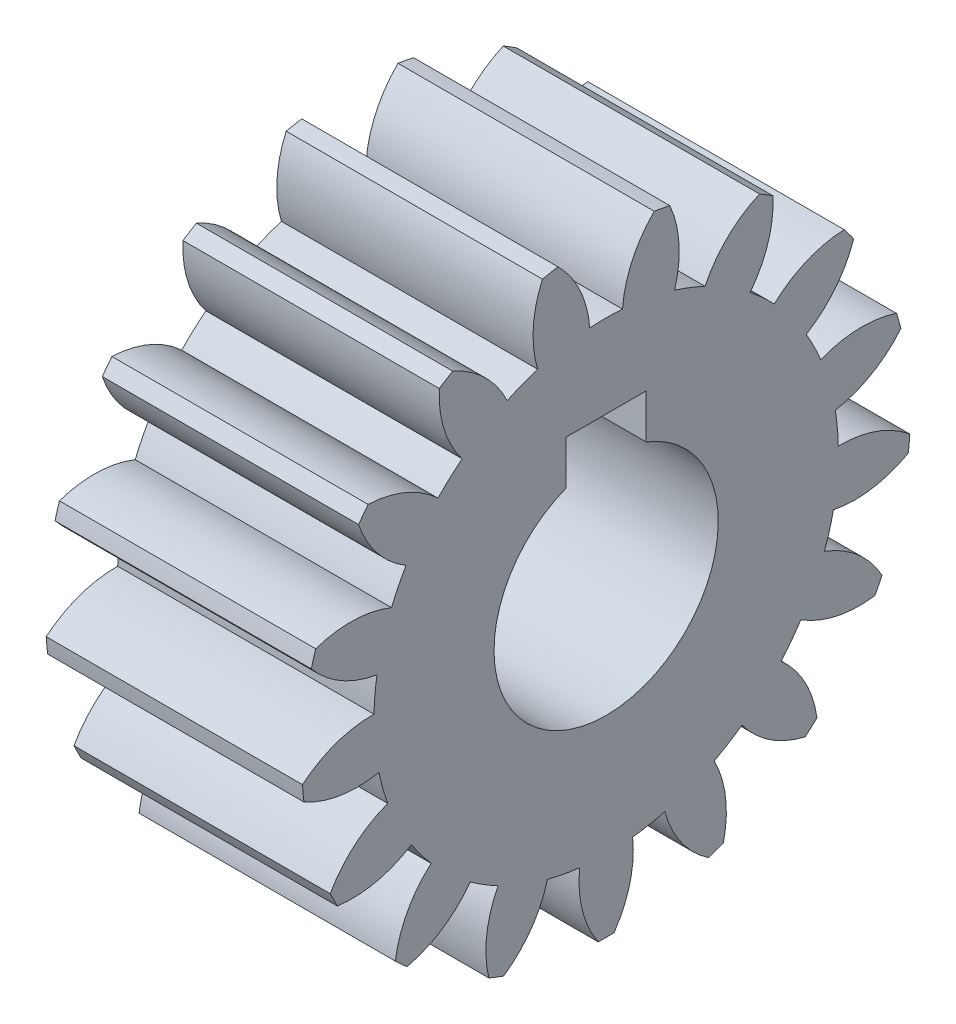
SolidWorks part; units mm, degrees
ref_plane "Plane1" through (0, 0, 0) normal (0, 0, 1) x (1, 0, 0)
ref_plane "Plane2" through (0, 0, 0) normal (0, 1, 0) x (1, 0, 0)
ref_plane "Plane3" through (0, 0, 0) normal (1, 0, 0) x (0, 0, -1)
sketch "HoldingSke" plane through (0, 0, 0) normal (0, 1, 0) x (1, 0, 0)
  line L0 (0, 0) -> (0.4782, -0.1462)
  line L1 (-15, 0) -> (100, 0) construction
  line L2 (0, 0) -> (-2.1039, 2.3779)
  line L3 (0, 0) -> (-11.863, 4.5341)
  line L4 (0, 0) -> (8.2586, 2.5249)
  line L5 (0, 0) -> (-46.8476, -17.4728)
  line L6 (0, 0) -> (-13.2634, -8.9489)
  line L7 (-2.1039, 2.3779) -> (8.6586, 51.2059)
  line L8 (-76.2, 54.61) -> (-73.9, 54.61)
  line L9 (-71.009, 38.7566) -> (-53.1078, 45.2721)
  line L10 (-76.2, 71.12) -> (104.1128, 71.12)
  line L11 (0, 0) -> (-16, 0)
  line L12 (-76.2, 101.6) -> (-76.133, 101.6)
  line L13 (24.9733, 27.94) -> (52.9518, 28.4284)
  line L14 (24.9733, 27.94) -> (24.9743, 27.94)
  line L15 (24.9733, 27.94) -> (100.4006, 29.5858)
  line L16 (-63.627, -2) -> (-12.827, -2)
  circle A0 centre (0, 0) radius 7
  circle A1 centre (0, 0) radius 14.499
  circle A2 centre (0, 0) radius 37.5
  circle A3 centre (0, 0) radius 7
  dimension "MHD" = 28.998
  dimension "Hub_dia" = 75
  dimension "Bore" = 14
  dimension "MBD" = 14
  dimension "Num_teeth" = 17
  dimension "Pitch" = 0.5
  dimension "Overall_len" = 50
  dimension "Show_teeth" = 17
  dimension "Thickness" = 16
  dimension "OAL" = 50.0001
  dimension "T_dim" = 2.3
  dimension "Ap" = 20
  dimension "H" = 19.05
  dimension "Pitch_radius" = 180.3128
  dimension "Width" = 16
  dimension "Backlash" = 0.067
  dimension "Addendum_fac" = 1
  dimension "Dedendum_fac" = 1.25
  dimension "Clearance_fac" = 0.25
  dimension "Dedendum_add" = 0.001
  dimension "Module" = 2
sketch "BasProSke" plane through (0, 0, 0) normal (0, 1, 0) x (1, 0, 0)
  line L0 (-10, 0) -> (60, 0) construction
  line L1 (0, 0) -> (0, 19)
  line L2 (0, 0) -> (16, 0)
  line L3 (16, 0) -> (16, 19)
  line L4 (16, 19) -> (0, 19)
  dimension "Thickness" = 16
  dimension "Diameter" = 38
revolve "Base-Revolve" add sketch "BasProSke" angle 360 about L0
sketch "TooCutSke" plane through (0, 0, 0) normal (1, 0, 0) x (0, 0, -1)
  line L1 (0, 0) -> (0, 107) construction
  line L2 (0, 0) -> (-1.6857, 16.9162) construction
  line L3 (0, 0) -> (-6.2247, 33.2991) construction
  line L4 (-1.6857, 16.9162) -> (-3.1123, 16.6495) construction
  arc A0 (1.0204, 14.4631) -> (-1.0204, 14.4631) centre (0, 0) ccw
  arc A1 (3.0261, 18.7832) -> (-3.0261, 18.7832) centre (0, 0) ccw
  circle A2 centre (0, 0) radius 17 construction
  circle A3 centre (0, 0) radius 15.9748 construction
  arc A4 (-1.0204, 14.4631) -> (-3.0261, 18.7832) centre (-7.8003, 13.9409) ccw
  arc A5 (3.0261, 18.7832) -> (1.0204, 14.4631) centre (7.8003, 13.9409) ccw
  dimension "Root_dia" = 28.998
  dimension "Overcut_dia" = 38.0508
  dimension "Pitch_dia" = 34
  dimension "Base_dia" = 31.9495
  dimension "Flank_rad" = 6.8
  dimension "Half_ang" = 10.588
  dimension "Half_CT" = 1.4513
extrude "ToothCut" cut sketch "TooCutSke" along normal through all
fillet "Breaks" [suppressed] radius 0.04
fillet "RootFillets" [suppressed] radius 0.501
pattern_circular "TeethCuts" count 17 every 21.176 about axis through (-10, 0, 0) along (1, 0, 0) of "ToothCut", "RootFillets", "Breaks"
sketch "HubNeaOneSke" plane through (0, 0, 0) normal (-1, 0, 0) x (0, 0, 1)
  circle A0 centre (0, 0) radius 14.499
  dimension "Diameter" = 28.998
extrude "HubNearOne" [suppressed] add sketch "HubNeaOneSke" along normal blind 34.0001
sketch "HubNeaBotSke" plane through (0, 0, 0) normal (-1, 0, 0) x (0, 0, 1)
  circle A0 centre (0, 0) radius 14.499
  dimension "Diameter" = 28.998
extrude "HubNearBoth" [suppressed] add sketch "HubNeaBotSke" along normal blind 17
ref_plane "FarPln" through (16, 0, 0) normal (1, 0, 0) x (0, 0, -1)
sketch "HubFarSke" plane through (16, 0, 0) normal (1, 0, 0) x (0, 0, -1)
  circle A0 centre (0, 0) radius 14.499
  dimension "Diameter" = 28.998
extrude "HubFar" [suppressed] add sketch "HubFarSke" along normal blind 17
sketch "BorSke" plane through (0, 0, 0) normal (1, 0, 0) x (0, 0, -1)
  circle A0 centre (0, 0) radius 7
  dimension "Diameter" = 14
extrude "Bore" cut sketch "BorSke" along normal mid plane 100.0001
sketch "KeySke" plane through (0, 0, 0) normal (1, 0, 0) x (0, 0, -1)
  line L0 (-2.5, 0) -> (-2.5, 9.3)
  line L1 (-2.5, 9.3) -> (2.5, 9.3)
  line L2 (2.5, 9.3) -> (2.5, 0)
  line L3 (0, 0) -> (0, 34) construction
  line L4 (-2.5, 0) -> (2.5, 0)
  dimension "Offset" = 9.3
  dimension "Width" = 5
extrude "Keyway" cut sketch "KeySke" along normal mid plane 100.0001
pattern_circular "Keyway2" [suppressed] count 2 every 90 about axis through (-10, 0, 0) along (1, 0, 0)
equation "' \"Module@HoldingSke\" = 6.35"
equation "' \"Num_teeth@HoldingSke\" = 12"
equation "' \"Ap@HoldingSke\" =  20"
equation "' \"Ap@HoldingSke\" = 20"
equation "' \"Width@HoldingSke\" = 0.5 * 25.4"
equation "' \"Hub_dia@HoldingSke\"= 1 * 25.4"
equation "' \"Hub_dia@HoldingSke\" = 1 * 25.4"
equation "' \"Overall_len@HoldingSke\" = 1.0 * 25.4"
equation "' \"Bore@HoldingSke\" = 0.75 * 25.4"
equation "' \"T_dim@HoldingSke\" = 0.1 * 25.4"
equation "' \"Width@KeySke\" = 0.25 * 25.4"
equation "' \"Show_teeth@HoldingSke\" = 13"
equation "' \"Backlash@HoldingSke\" = 0.009 * 25.4"
equation "' \"Addendum_fac@HoldingSke\" = 1.0"
equation "' \"Dedendum_fac@HoldingSke\" = 1.25"
equation "' \"Dedendum_add@HoldingSke\" = 0.00005 * 25.4"
equation "' \"Clearance_fac@HoldingSke\" = 0.25"
equation "\"Pitch@HoldingSke\" = 1 / \"Module@HoldingSke\""
equation "\"Overcut_dia@TooCutSke\" = (\"Num_teeth@HoldingSke\" + 2 * \"Addendum_fac@HoldingSke\") / \"Pitch@HoldingSke\" + 0.002 * 25.4"
equation "\"Pitch_dia@TooCutSke\" = \"Num_teeth@HoldingSke\" / \"Pitch@HoldingSke\""
equation "\"Base_dia@TooCutSke\" = \"Num_teeth@HoldingSke\" / \"Pitch@HoldingSke\" * cos((\"Ap@HoldingSke\"  * 3.14159265 / 180))"
equation "\"Root_dia@TooCutSke\" = (\"Num_teeth@HoldingSke\" + 2) / \"Pitch@HoldingSke\" - 2 * (\"Addendum_fac@HoldingSke\" + \"Dedendum_fac@HoldingSke\") / \"Pitch@HoldingSke\" - \"Dedendum_add@HoldingSke\" * 2"
equation "\"Half_ang@TooCutSke\" = 180 / \"Num_teeth@HoldingSke\""
equation "\"Half_CT@TooCutSke\" = \"Num_teeth@HoldingSke\" / \"Pitch@HoldingSke\" * sin((3.14159265 / 2 / \"Num_teeth@HoldingSke\")) / 2 - 7 * \"Backlash@HoldingSke\" / 4"
equation "\"Flank_rad@TooCutSke\" = \"Num_teeth@HoldingSke\" / \"Pitch@HoldingSke\" / 5"
equation "\"Radius@RootFillets\" = \"Clearance_fac@HoldingSke\" / \"Pitch@HoldingSke\" + \"Dedendum_add@HoldingSke\""
equation "\"Break_rad@Breaks\" = 0.02 / \"Pitch@HoldingSke\""
equation "\"Thickness@HoldingSke\" = \"Width@HoldingSke\""
equation "\"OAL@HoldingSke\" = \"Thickness@HoldingSke\""
equation "\"MHD@HoldingSke\" = (\"Num_teeth@HoldingSke\" + 2) / \"Pitch@HoldingSke\" - 2 * (\"Addendum_fac@HoldingSke\" + \"Dedendum_fac@HoldingSke\")  / \"Pitch@HoldingSke\" - \"Dedendum_add@HoldingSke\" * 2"
equation "\"MBD@HoldingSke\" = (\"Num_teeth@HoldingSke\" + 2) / \"Pitch@HoldingSke\" - 2 * (\"Addendum_fac@HoldingSke\" + \"Dedendum_fac@HoldingSke\")  / \"Pitch@HoldingSke\" - \"Dedendum_add@HoldingSke\" * 2 - 0.002 * 25.4"
equation "\"MHD@HoldingSke\" = ((sgn( \"MHD@HoldingSke\" - \"Hub_dia@HoldingSke\" )-1)*( \"MHD@HoldingSke\" - \"Hub_dia@HoldingSke\" ))/-2+ \"Hub_dia@HoldingSke\""
equation "\"MBD@HoldingSke\" = ((sgn( \"MBD@HoldingSke\" - \"Bore@HoldingSke\" )-1)*( \"MBD@HoldingSke\" - \"Bore@HoldingSke\" ))/-2+ \"Bore@HoldingSke\""
equation "\"OAL@HoldingSke\" = ((sgn( \"OAL@HoldingSke\" - \"Overall_len@HoldingSke\" )+1)*( \"OAL@HoldingSke\" - \"Overall_len@HoldingSke\" ))/2 + \"Overall_len@HoldingSke\" + 0.000002 * 25.4"
equation "\"Num_teeth@TeethCuts\" = int( \"Show_teeth@HoldingSke\" ) + 1"
equation "\"Num_teeth@TeethCuts\" = ((sgn( \"Num_teeth@TeethCuts\" - \"Num_teeth@HoldingSke\" )-1)*( \"Num_teeth@TeethCuts\" - \"Num_teeth@HoldingSke\" ))/-2+ \"Num_teeth@HoldingSke\""
equation "\"Num_teeth@TeethCuts\" = ((sgn( \"Num_teeth@TeethCuts\" - 2.0)+1)*( \"Num_teeth@TeethCuts\" - 2.0))/2 +2.0"
equation "\"Angle@TeethCuts\" = 360.0 / \"Num_teeth@HoldingSke\""
equation "\"Diameter@BasProSke\" = (\"Num_teeth@HoldingSke\" + 2 * \"Addendum_fac@HoldingSke\") / \"Pitch@HoldingSke\""
equation "\"Thickness@BasProSke\"  = \"Thickness@HoldingSke\""
equation "' \"Fillet_rad@BasProSke\" =  \"Thickness@HoldingSke\" * 0.05"
equation "' \"Fillet_rad@BasProSke\" = \"Thickness@HoldingSke\" * 0.05"
equation "\"MHD@HoldingSke\" = ((sgn( \"MHD@HoldingSke\" - \"Root_dia@TooCutSke\" )-1)*( \"MHD@HoldingSke\" - \"Root_dia@TooCutSke\" ))/-2+ \"Root_dia@TooCutSke\""
equation "\"Diameter@HubNeaOneSke\" = \"MHD@HoldingSke\""
equation "\"Length@HubNearOne\" = \"OAL@HoldingSke\" - \"Thickness@BasProSke\""
equation "\"Diameter@HubNeaBotSke\" = \"MHD@HoldingSke\""
equation "\"Length@HubNearBoth\" = ( \"OAL@HoldingSke\" - \"Thickness@BasProSke\" ) / 2.0"
equation "\"Thickness@FarPln\" = \"Thickness@BasProSke\""
equation "\"Diameter@HubFarSke\" = \"MHD@HoldingSke\""
equation "\"Length@HubFar\" = ( \"OAL@HoldingSke\" - \"Thickness@BasProSke\" ) / 2.0"
equation "\"Diameter@BorSke\" = \"MBD@HoldingSke\""
equation "\"D1@Bore\" = \"OAL@HoldingSke\" * 2.0"
equation "\"D1@Keyway\" = \"OAL@HoldingSke\" * 2.0"
equation "\"Offset@KeySke\" = \"T_dim@HoldingSke\" + \"MBD@HoldingSke\" / 2.0"
